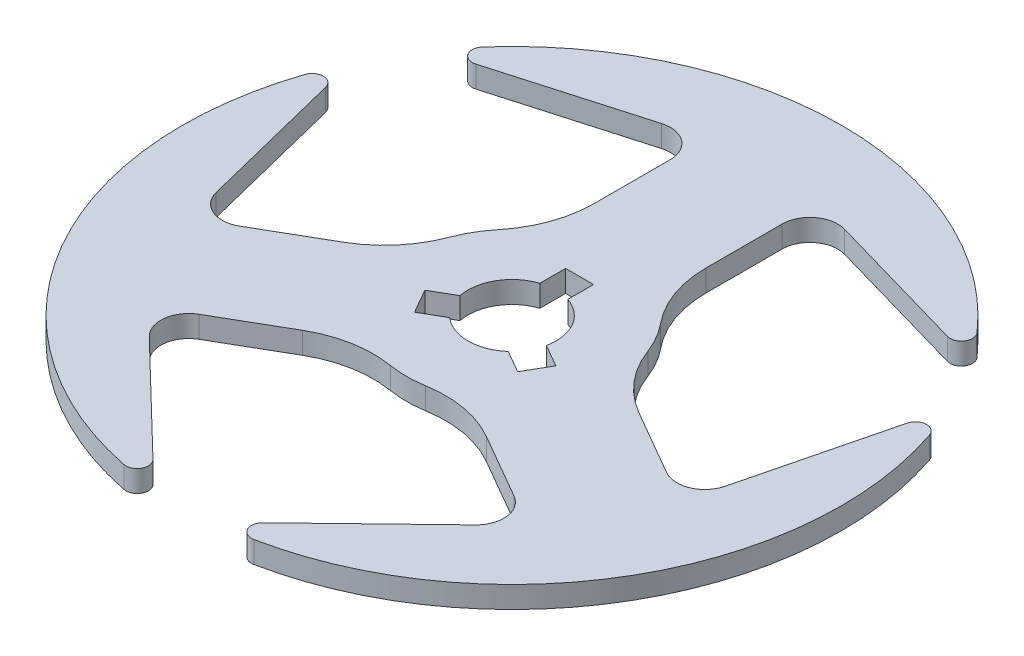
SolidWorks part; units mm, degrees
ref_plane "Front Plane" through (0, 0, 0) normal (0, 0, 1) x (1, 0, 0)
ref_plane "Top Plane" through (0, 0, 0) normal (0, 1, 0) x (1, 0, 0)
ref_plane "Right Plane" through (0, 0, 0) normal (1, 0, 0) x (0, 0, -1)
sketch "Sketch1" plane through (0, 0, 0) normal (0, 1, 0) x (1, 0, 0)
  line L0 (-1.27, 4.8706) -> (-1.27, 2.0368)
  line L1 (1.27, 4.8706) -> (1.27, 2.0368)
  line L2 (-5.3631, 4.5396) -> (-2.08, 5.481)
  line L3 (2.08, 5.481) -> (5.3631, 4.5396)
  arc A0 (5.6238, 4.9516) -> (-5.6238, 4.9516) centre (0, 0) ccw
  circle A1 centre (0, 0) radius 2.4003
  arc A2 (-2.08, 5.481) -> (-1.27, 4.8706) centre (-1.905, 4.8706) cw
  arc A3 (1.27, 4.8706) -> (2.08, 5.481) centre (1.905, 4.8706) cw
  arc A4 (-5.6238, 4.9516) -> (-5.3631, 4.5396) centre (-5.4331, 4.7837) ccw
  arc A5 (5.6238, 4.9516) -> (5.3631, 4.5396) centre (5.4331, 4.7837) cw
  dimension "D1" = 14.986
  dimension "D6" = 4.8006
  dimension "D9" = 0.635
  dimension "D10" = 0.254
  dimension "D2" = 74
  dimension "D3" = 74
  dimension "D4" = 2.54
  dimension "D5" = 1.27
  dimension "D7" = 5.842
  dimension "D8" = 5.842
extrude "Boss-Extrude1" add sketch "Sketch1" along normal blind 0.4933 contours A5 A0 A4 L2 A2 L0 A1 L1 A3 L3 | A1
pattern_circular "CirPattern1" count 3 over 360 about axis through (0, 0, 0) along (0, 1, 0) of "Boss-Extrude1"
sketch "Sketch2" plane through (0, 0.4933, 0) normal (0, 1, 0) x (1, 0, 0)
  line L0 (0.3175, 1.5367) -> (-0.3175, 1.5367)
  line L1 (-0.3175, 1.5367) -> (-0.3175, 0.9517)
  line L2 (0.3175, 1.5367) -> (0.3175, 0.9517)
  circle A0 centre (0, 0) radius 1.0033
  dimension "D4" = 2.0066
  dimension "D1" = 0.635
  dimension "D2" = 0.3175
  dimension "D3" = 2.54
extrude "Cut-Extrude3" cut sketch "Sketch2" along direction (0, -1, 0) on the side against the normal through all contours A0 | A0 L2 L0 L1
pattern_circular "CirPattern2" count 3 over 360 about axis through (0, 0, 0) along (0, 1, 0) of "Cut-Extrude3"
fillet "Fillet1" radius 2.54 6 edges at (-1.27, 0.2466, -2.0368) (-2.3989, 0.2466, -0.0815) (-1.1289, 0.2466, 2.1183) (1.1289, 0.2466, 2.1183) (2.3989, 0.2466, -0.0815) (1.27, 0.2466, -2.0368)
ref_plane "Plane1" through (0, 0, 0) normal (0.5, 0, 0.866) x (0.866, 0, -0.5)
